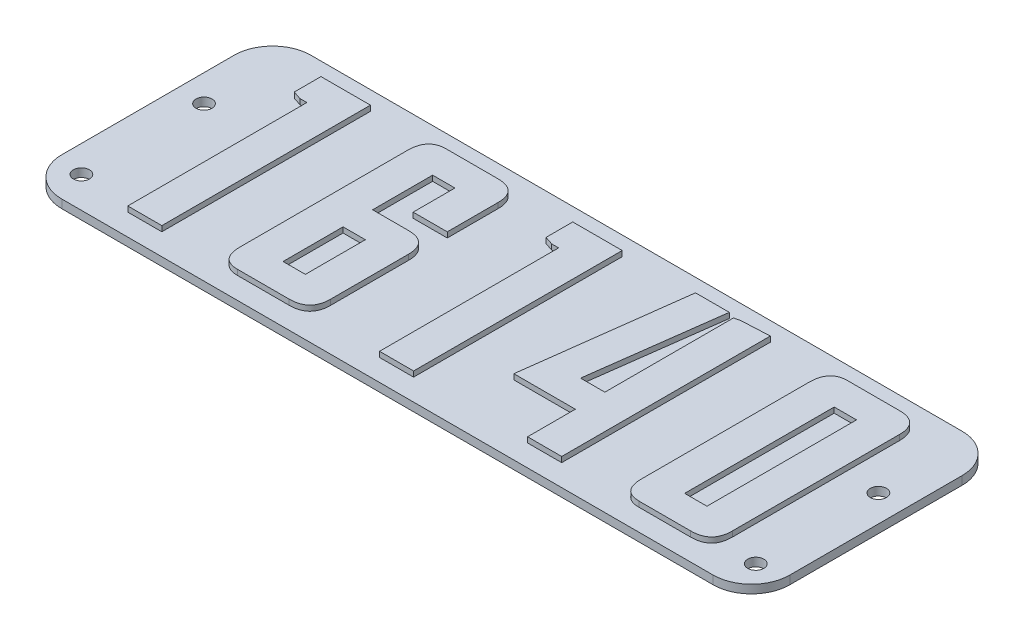
SolidWorks part; units mm, degrees
ref_plane "Front" through (0, 0, 0) normal (0, 0, 1) x (1, 0, 0)
ref_plane "Top" through (0, 0, 0) normal (0, 1, 0) x (1, 0, 0)
ref_plane "Right" through (0, 0, 0) normal (1, 0, 0) x (0, 0, -1)
sketch "Sketch1" plane through (0, 0, 0) normal (0, 1, 0) x (1, 0, 0)
  line L0 (0, 0) -> (0, 50000) construction
  line L1 (-95, -32.5) -> (95, -32.5)
  line L2 (-95, -32.5) -> (-95, 32.5)
  line L3 (-95, 32.5) -> (95, 32.5)
  line L4 (95, -32.5) -> (95, 32.5)
  circle A0 centre (-88, 7.6232) radius 2.1
  circle A1 centre (-88, -24.3768) radius 2.1
  circle A2 centre (88, -24.3768) radius 2.1
  circle A3 centre (88, 7.6232) radius 2.1
  point P0 (0, 0)
  point P5 (0, 0)
extrude "Boss-Extrude1" add sketch "Sketch1" along normal blind 2.2
sketch "Sketch3" plane through (0, 2.2, 0) normal (0, 1, 0) x (1, 0, 0)
  text T0 "<b>16140</b>" font "ViolentaSolidW01-Regular" height in points 150
extrude "Boss-Extrude3" add sketch "Sketch3" along normal blind 1.4
fillet "Fillet1" radius 10 4 edges at (95, 1.1, 32.5) (-95, 1.1, 32.5) (95, 1.1, -32.5) (-95, 1.1, -32.5)
